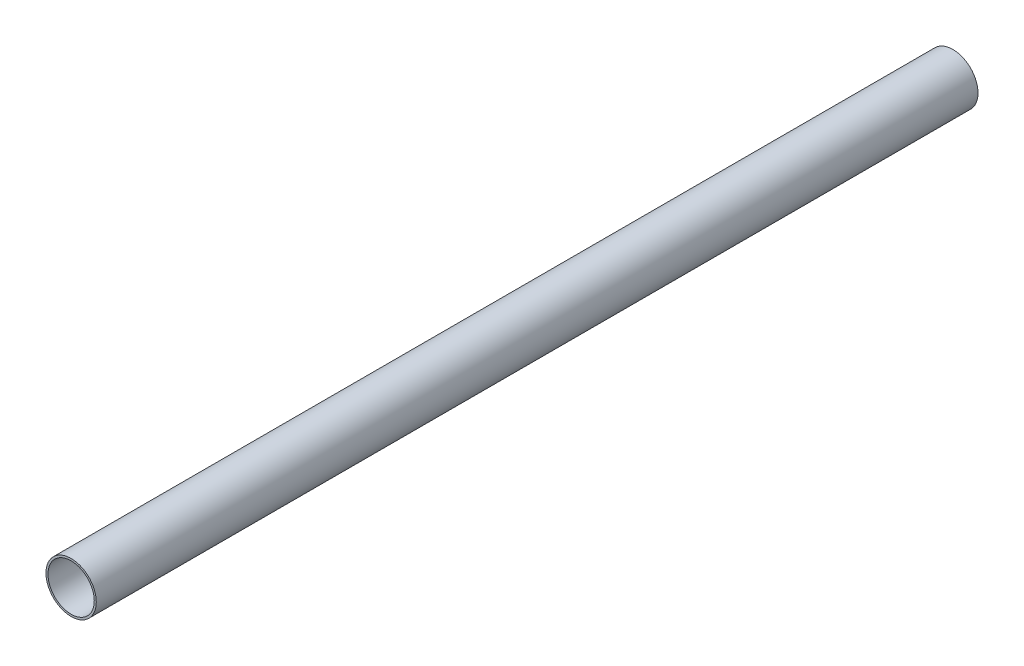
SolidWorks part; units mm, degrees
material "Thornel Mat VMA"
ref_plane "前视基准面" through (0, 0, 0) normal (0, 0, 1) x (1, 0, 0)
ref_plane "上视基准面" through (0, 0, 0) normal (0, 1, 0) x (1, 0, 0)
ref_plane "右视基准面" through (0, 0, 0) normal (1, 0, 0) x (0, 0, -1)
sketch "草图1" plane through (0, 0, 0) normal (0, 0, 1) x (1, 0, 0)
  circle A0 centre (0, 0) radius 12.5
  circle A1 centre (0, 0) radius 11.5
  dimension "D1" = 25
  dimension "D2" = 1
extrude "凸台-拉伸1" add sketch "草图1" along normal mid plane 438
